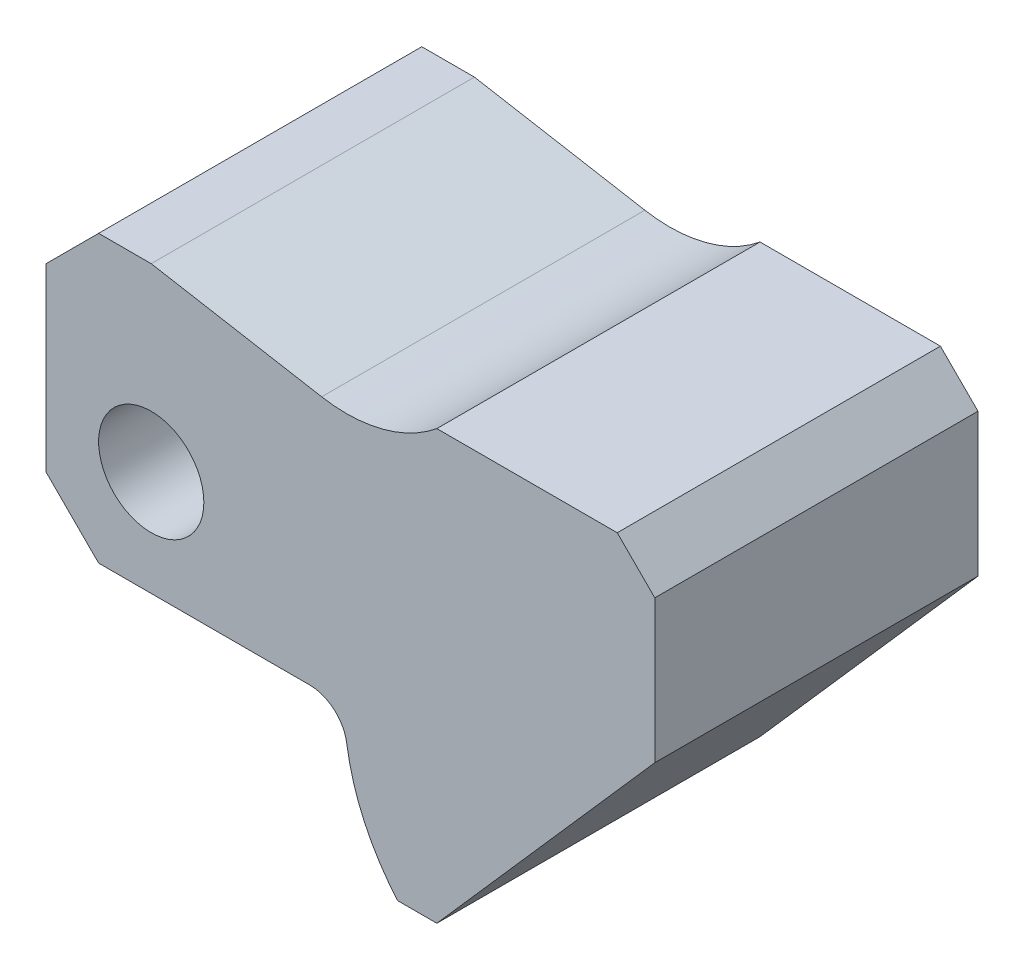
SolidWorks part; units mm, degrees
material "AISI 1020"
ref_plane "Front Plane" through (0, 0, 0) normal (0, 0, 1) x (1, 0, 0)
ref_plane "Top Plane" through (0, 0, 0) normal (0, 1, 0) x (1, 0, 0)
ref_plane "Right Plane" through (0, 0, 0) normal (1, 0, 0) x (0, 0, -1)
sketch "Sketch1" plane through (0, 0, 0) normal (0, 0, 1) x (1, 0, 0)
  line L1 (-14, 24) -> (67, 24)
  line L2 (-14, 24) -> (-14, -33)
  line L3 (-14, -33) -> (67, -33)
  line L4 (67, 24) -> (67, -33)
  dimension "D1" = 57
  dimension "D2" = 81
  dimension "D3" = 14
  dimension "D4" = 24
extrude "Boss-Extrude1" add sketch "Sketch1" along normal blind 43
sketch "Sketch2" plane through (0, 0, 0) normal (0, 0, 1) x (1, 0, 0)
  line L0 (38, -33) -> (67, 0)
  line L1 (-14, -33) -> (67, -33) construction
  line L2 (67, -33) -> (67, 24) construction
  line L3 (67, 0) -> (92.5631, 0)
  line L4 (92.5631, 0) -> (92.5631, -46.2472)
  line L5 (92.5631, -46.2472) -> (38, -46.2472)
  line L6 (38, -46.2472) -> (38, -33)
  line L7 (67, 24) -> (-14, 24) construction
  dimension "D1" = 24
  dimension "D2" = 29
extrude "Cut-Extrude1" cut sketch "Sketch2" against normal through all both and the other way through all
sketch "Sketch3" plane through (0, 0, 0) normal (0, 0, 1) x (1, 0, 0)
  line L0 (67, 19) -> (62, 24)
  line L1 (67, 0) -> (67, 24) construction
  line L2 (67, 24) -> (-14, 24) construction
  line L3 (62, 24) -> (62, 35.074)
  line L4 (62, 35.074) -> (76.3941, 35.074)
  line L5 (76.3941, 35.074) -> (76.3941, 19)
  line L6 (76.3941, 19) -> (67, 19)
  line L8 (-30.3655, -14) -> (25.697, -14)
  line L9 (-30.3655, -14) -> (-30.3655, -63.1573)
  line L10 (-30.3655, -63.1573) -> (25.697, -63.1573)
  line L11 (25.697, -14) -> (25.697, -63.1573)
  line L12 (-14, -33) -> (38, -33) construction
  line L13 (38, -33) -> (72.4867, -33) construction
  line L14 (54.697, -33) -> (54.697, -14) construction
  line L15 (67, 0) -> (38, -33) construction
  dimension "D3" = 29
  dimension "D1" = 19
  dimension "D2" = 19
  dimension "D4" = 5
  dimension "D5" = 45
extrude "Cut-Extrude2" cut sketch "Sketch3" against normal through all both and the other way through all
sketch "Sketch4" plane through (0, 0, 0) normal (0, 0, 1) x (1, 0, 0)
  line L1 (54.697, -33) -> (54.697, -14) construction
  line L2 (67, 0) -> (38, -33) construction
  line L3 (-14, -7) -> (-7, -14)
  line L4 (-14, 24) -> (-14, -14) construction
  line L5 (25.697, -14) -> (-14, -14) construction
  line L6 (-7, -14) -> (-7, -25.5815)
  line L7 (-7, -25.5815) -> (-25.6988, -25.5815)
  line L8 (-25.6988, -25.5815) -> (-25.6988, 4.6988)
  line L9 (-14, -7) -> (-25.6988, 4.6988)
  line L10 (25.697, -14) -> (1.83, -60.1458)
  line L11 (1.83, -60.1458) -> (54.697, -43)
  arc A0 (25.697, -14) -> (54.697, -43) centre (54.697, -14) ccw
  circle A1 centre (0, 0) radius 7
  dimension "D2" = 29
  dimension "D3" = 14
  dimension "D4" = 45
  dimension "D1" = 19
  dimension "D5" = 7
extrude "Cut-Extrude4" cut sketch "Sketch4" against normal through all both and the other way through all
fillet "Fillet1" radius 5 1 edges
sketch "Sketch5" plane through (0, 0, 0) normal (0, 0, 1) x (1, 0, 0)
  line L0 (-14, 17) -> (-7, 24)
  line L1 (-14, 24) -> (-14, -7) construction
  line L2 (62, 24) -> (-14, 24) construction
  line L3 (-7, 24) -> (-7, 33.911)
  line L4 (-7, 33.911) -> (-24.7733, 33.911)
  line L5 (-24.7733, 33.911) -> (-24.7733, 17)
  line L6 (-24.7733, 17) -> (-14, 17)
  dimension "D1" = 7
  dimension "D2" = 45
extrude "Cut-Extrude5" cut sketch "Sketch5" against normal through all both and the other way through all
sketch "Sketch6" plane through (0, 0, 0) normal (0, 0, 1) x (1, 0, 0)
  line L0 (38, 24) -> (38, 44.4565) construction
  line L1 (62, 24) -> (-7, 24) construction
  line L4 (67, 0) -> (67, 19) construction
  line L5 (0, 24) -> (0, 44.4565) construction
  line L6 (-14, 17) -> (-14, -7) construction
  line L7 (0, 24) -> (21.908, 20.137) construction
  circle A1 centre (25.9775, 38.7126) radius 19
  point P10 (0, 0)
  dimension "D2" = 14
  dimension "D4" = 19
  dimension "D1" = 29
  dimension "D3" = 10
extrude "Cut-Extrude7" cut sketch "Sketch6" against normal through all both and the other way through all contours A1
sketch "Sketch7" plane through (0, 0, 0) normal (0, 0, 1) x (1, 0, 0)
  line L0 (0, 24) -> (0, 37.9059)
  line L1 (13.955, 24) -> (-7, 24) construction
  line L2 (-14, 17) -> (-14, -7) construction
  line L3 (0, 24) -> (22.6782, 20.0012)
  line L4 (23.4786, 19.8776) -> (0, 37.9059)
  arc A0 (13.955, 24) -> (38, 24) centre (25.9775, 38.7126) ccw construction
  dimension "D1" = 14
  dimension "D2" = 10
extrude "Cut-Extrude8" cut sketch "Sketch7" against normal through all both and the other way through all
equation "\"B\" = 59mm"
equation "\"A\" = 84mm"
equation "\"C\"= 45mm"
